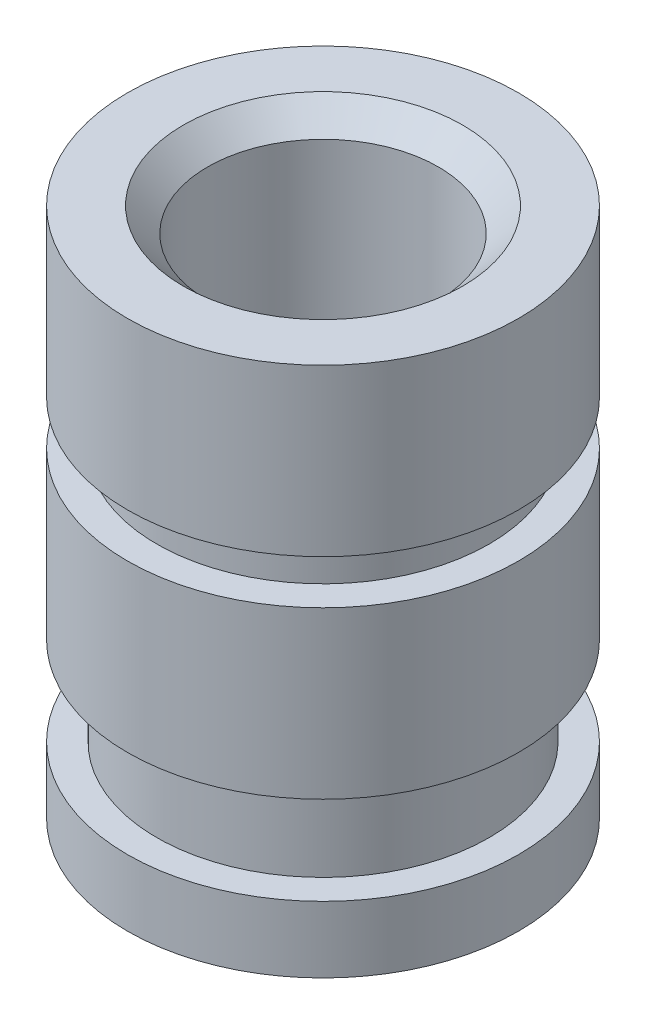
SolidWorks part; units mm, degrees
material "Brass"
ref_plane "Front Plane" through (0, 0, 0) normal (0, 0, 1) x (1, 0, 0)
ref_plane "Top Plane" through (0, 0, 0) normal (0, 1, 0) x (1, 0, 0)
ref_plane "Right Plane" through (0, 0, 0) normal (1, 0, 0) x (0, 0, -1)
sketch "Sketch2" plane through (0, 0, 0) normal (0, 0, 1) x (1, 0, 0)
  line L0 (0, -157.4394) -> (0, 7714.5321) construction
  line L1 (0, 0) -> (3.5, 0)
  line L2 (3.5, 0) -> (3.5, 1.188)
  line L3 (3.5, 1.188) -> (2.975, 1.188)
  line L4 (2.975, 1.188) -> (2.975, 2.771)
  line L5 (2.975, 2.771) -> (3.5, 2.771)
  line L6 (3.5, 2.771) -> (3.5, 5.74)
  line L7 (3.5, 5.74) -> (2.975, 5.74)
  line L8 (2.975, 5.74) -> (2.975, 6.532)
  line L9 (2.975, 6.532) -> (3.5, 6.532)
  line L10 (3.5, 6.532) -> (3.5, 9.501)
  line L11 (3.5, 9.501) -> (0, 9.501)
  line L12 (0, 9.501) -> (0, 0)
  dimension "D1" = 1.188
  dimension "D2" = 7
  dimension "D3" = 5.95
  dimension "D4" = 1.583
  dimension "D5" = 2.969
  dimension "D6" = 2.969
  dimension "D7" = 0.792
revolve "Revolve1" add sketch "Sketch2" angle 360 about L0
sketch "Sketch3" plane through (0, 9.501, 0) normal (0, 1, 0) x (1, 0, 0)
  circle A0 centre (0, 0) radius 2.067
  dimension "D1" = 4.134
extrude "Cut-Extrude1" cut sketch "Sketch3" against normal up to next
sketch "Sketch14" plane through (0, 0, 0) normal (0, 0, 1) x (1, 0, 0)
  line L0 (0, -1000) -> (0, 49000) construction
  line L1 (-2.5, 9.501) -> (-2.067, 9.068)
  line L3 (-2.067, 9.068) -> (-2.067, 9.501)
  line L4 (3.5, 9.501) -> (-3.5, 9.501) construction
  line L5 (-2.067, 9.501) -> (-2.5, 9.501)
  line L6 (-2.5, 0) -> (-2.067, 0.433)
  line L7 (-3.5, 0) -> (3.5, 0) construction
  line L8 (-2.067, 0.433) -> (-2.067, 0)
  line L9 (-2.067, 0) -> (-2.5, 0)
  dimension "D1" = 5
  dimension "D2" = 45
  dimension "D3" = 4.134
  dimension "D4" = 5
  dimension "D5" = 4.134
  dimension "D6" = 45
revolve "Cut-Revolve1" cut sketch "Sketch14" angle 360 about L0
